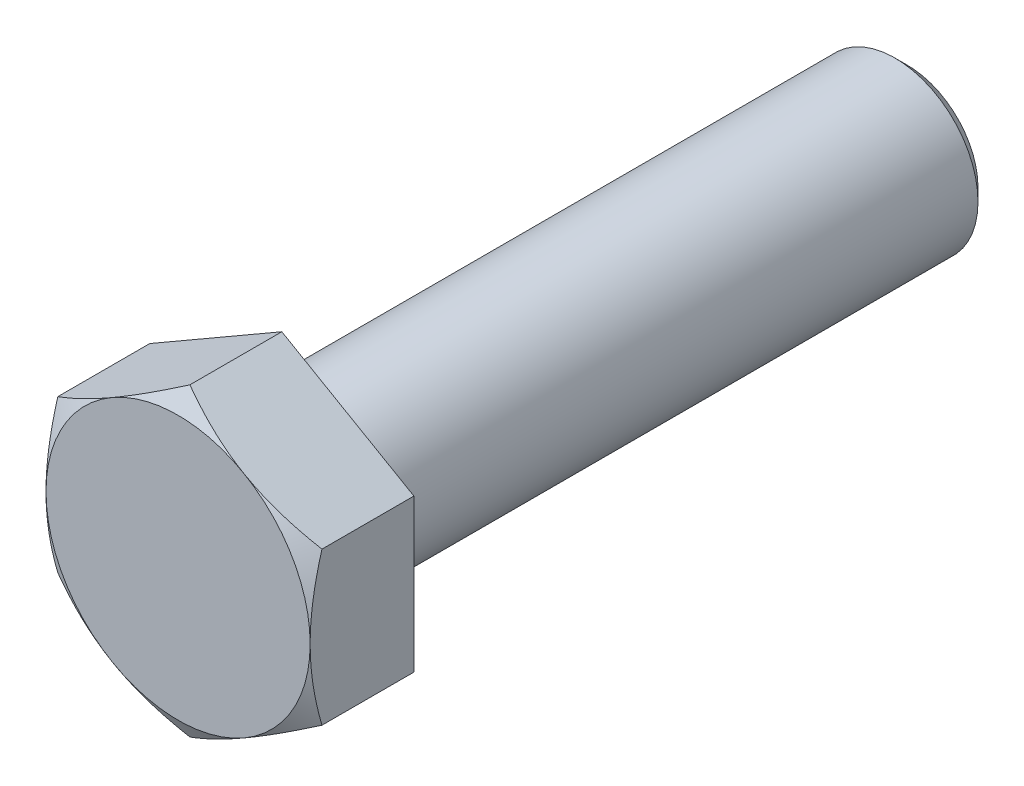
SolidWorks part; units mm, degrees
ref_plane "Front Plane" through (0, 0, 0) normal (0, 0, 1) x (1, 0, 0)
ref_plane "Top Plane" through (0, 0, 0) normal (0, 1, 0) x (1, 0, 0)
ref_plane "Right Plane" through (0, 0, 0) normal (1, 0, 0) x (0, 0, -1)
sketch "Sketch1" plane through (0, 0, 0) normal (0, 0, 1) x (1, 0, 0)
  line L0 (0, 0) -> (0, 7.3497) construction
  line L2 (0, 7.3497) -> (-6.365, 3.6748)
  line L3 (-6.365, 3.6748) -> (-6.365, -3.6748)
  line L4 (-6.365, -3.6748) -> (0, -7.3497)
  line L5 (0, -7.3497) -> (6.365, -3.6748)
  line L6 (6.365, -3.6748) -> (6.365, 3.6748)
  line L7 (6.365, 3.6748) -> (0, 7.3497)
  circle A0 centre (0, 0) radius 6.365 construction
  dimension "HEX" = 12.73
extrude "Boss-Extrude1" add sketch "Sketch1" along normal blind 5.15
sketch "Sketch2" plane through (0, 0, 0) normal (1, 0, 0) x (0, 0, -1)
  line L0 (0, 0) -> (30, 0) construction
  line L1 (0, 0) -> (0, 4.6)
  line L4 (29.4, 4) -> (30, 3.4)
  line L7 (30, 3.4) -> (30, 0)
  line L8 (30, 0) -> (0, 0)
  line L9 (29.4, 4) -> (0.6, 4)
  arc A3 (0.6, 4) -> (0, 4.6) centre (0.6, 4.6) cw
  dimension "LENGTH" = 30
  dimension "WIDTH2" = 6.8
  dimension "WIDTH1" = 8
  dimension "D5" = 45
  dimension "DA" = 9.2
revolve "Revolve1" add sketch "Sketch2" angle 360 about L0
cosmetic thread "Cosmetic Thread1" parameters "D1"=46.25, "D2"=8
sketch "Sketch3" plane through (0, 0, 0) normal (1, 0, 0) x (0, 0, -1)
  line L0 (-12.2049, 0) -> (129.7862, 0) construction
  line L1 (-5.15, 7.3497) -> (-4.5815, 7.3497)
  line L2 (-0.15, 7.3497) -> (-0.15, 5.8866)
  line L3 (-4.5815, 7.3497) -> (-5.15, 6.365)
  line L4 (-0.15, 5.8866) -> (0, 5.8)
  line L5 (-5.15, 6.365) -> (-5.15, 7.3497)
  line L6 (0, -3.6748) -> (0, 3.6748) construction
  line L7 (-5.15, 7.3497) -> (0, 7.3497) construction
  line L8 (-5.15, 3.6748) -> (-5.15, 7.3497) construction
  line L10 (0, 5.8) -> (0, 7.3497)
  line L11 (0, 7.3497) -> (-0.15, 7.3497)
  dimension "D1" = 30
  dimension "SAME AS HEX" = 12.73
  dimension "D3" = 30
  dimension "C" = 0.15
  dimension "DW" = 11.6
revolve "Cut-Revolve1" cut sketch "Sketch3" angle 360 about L0
